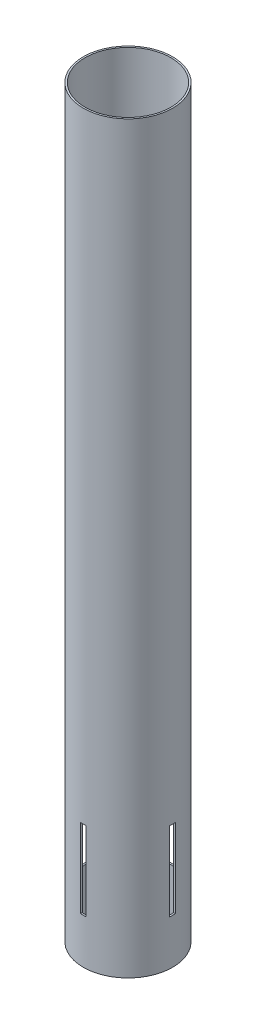
SolidWorks part; units mm, degrees
ref_plane "Front Plane" through (0, 0, 0) normal (0, 0, 1) x (1, 0, 0)
ref_plane "Top Plane" through (0, 0, 0) normal (0, 1, 0) x (1, 0, 0)
ref_plane "Right Plane" through (0, 0, 0) normal (1, 0, 0) x (0, 0, -1)
sketch "Sketch1" plane through (0, 0, 0) normal (0, 1, 0) x (1, 0, 0)
  circle A0 centre (0, 0) radius 39.6
  circle A1 centre (0, 0) radius 38.1
  dimension "D1" = 79.2
  dimension "D2" = 76.2
extrude "Boss-Extrude1" add sketch "Sketch1" along normal blind 660
sketch "Sketch2" plane through (0, 0, 0) normal (0, 0, 1) x (1, 0, 0)
  line L1 (-2.5, 40) -> (2.5, 40)
  line L2 (-2.5, 40) -> (-2.5, 110)
  line L3 (-2.5, 110) -> (2.5, 110)
  line L4 (2.5, 40) -> (2.5, 110)
  point P4 (0, 40)
  dimension "D1" = 40
  dimension "D2" = 70
  dimension "D3" = 5
extrude "Cut-Extrude1" cut sketch "Sketch2" against normal through all
pattern_circular "CirPattern1" count 4 over 360 about axis through (0, 0, 0) along (0, 1, 0) of "Cut-Extrude1"
